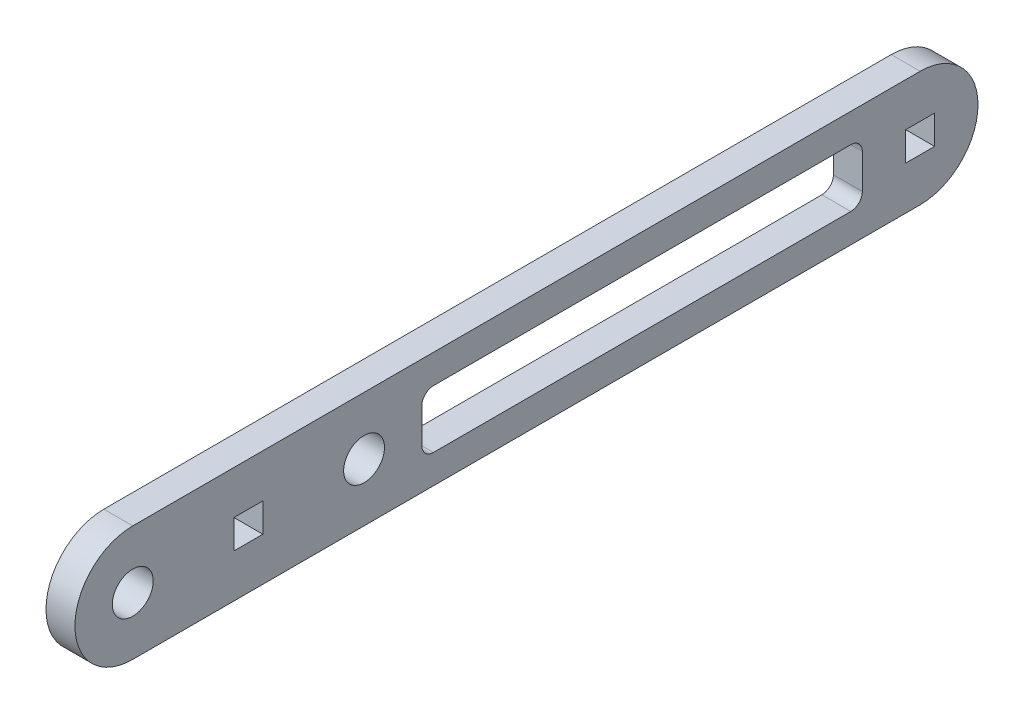
SolidWorks part; units mm, degrees
material "Custom Plastic"
ref_plane "Front Plane" through (0, 0, 0) normal (0, 0, 1) x (1, 0, 0)
ref_plane "Top Plane" through (0, 0, 0) normal (0, 1, 0) x (1, 0, 0)
ref_plane "Right Plane" through (0, 0, 0) normal (1, 0, 0) x (0, 0, -1)
sketch "Sketch1" plane through (0, 0, 0) normal (1, 0, 0) x (0, 0, -1)
  line L0 (0, 0) -> (-73.7616, 0) construction
  line L1 (-88.0491, -1.5875) -> (-84.8741, 1.5875) construction
  line L2 (-72.1741, -1.5875) -> (-75.3491, -1.5875)
  line L3 (-72.1741, -1.5875) -> (-72.1741, 1.5875)
  line L4 (-72.1741, 1.5875) -> (-75.3491, 1.5875)
  line L5 (-75.3491, -1.5875) -> (-75.3491, 1.5875)
  line L6 (-72.1741, -1.5875) -> (-75.3491, 1.5875) construction
  line L7 (-72.1741, 1.5875) -> (-75.3491, -1.5875) construction
  line L8 (-62.6491, -1.5875) -> (-59.4741, 1.5875) construction
  line L9 (-86.4616, 0) -> (-73.7616, 0) construction
  line L10 (-86.4616, 6.35) -> (0, 6.35)
  line L11 (-86.4616, 6.35) -> (-86.4616, 0) construction
  line L12 (0, -6.35) -> (-86.4616, -6.35)
  line L13 (-86.4616, 0) -> (-86.4616, -6.35) construction
  line L14 (-54.7116, 0) -> (-54.7116, 1.905)
  line L15 (-53.4416, 3.175) -> (-7.62, 3.175)
  line L16 (-6.35, 1.905) -> (-6.35, -1.905)
  line L17 (-7.62, -3.175) -> (-53.4416, -3.175)
  line L18 (-54.7116, -1.905) -> (-54.7116, 0)
  line L20 (1.5875, -1.5875) -> (-1.5875, -1.5875)
  line L21 (1.5875, -1.5875) -> (1.5875, 1.5875)
  line L22 (1.5875, 1.5875) -> (-1.5875, 1.5875)
  line L23 (-1.5875, -1.5875) -> (-1.5875, 1.5875)
  line L24 (1.5875, -1.5875) -> (-1.5875, 1.5875) construction
  line L25 (1.5875, 1.5875) -> (-1.5875, -1.5875) construction
  circle A0 centre (-61.0616, 0) radius 2.2451
  circle A1 centre (-86.4616, 0) radius 2.2451
  circle A2 centre (0, 0) radius 2.2451 construction
  arc A3 (-86.4616, 6.35) -> (-86.4616, -6.35) centre (-86.4616, 0) ccw
  arc A4 (0, 6.35) -> (0, -6.35) centre (0, 0) cw
  arc A5 (-7.62, 3.175) -> (-6.35, 1.905) centre (-7.62, 1.905) cw
  arc A6 (-6.35, -1.905) -> (-7.62, -3.175) centre (-7.62, -1.905) cw
  arc A7 (-53.4416, -3.175) -> (-54.7116, -1.905) centre (-53.4416, -1.905) cw
  arc A8 (-54.7116, 1.905) -> (-53.4416, 3.175) centre (-53.4416, 1.905) cw
  circle A9 centre (-73.7616, 0) radius 2.2451 construction
  dimension "D5" = 6.35
  dimension "D9" = 1.27
  dimension "D1" = 73.7616
  dimension "D2" = 3.175
  dimension "D3" = 12.7
  dimension "D4" = 12.7
  dimension "D6" = 6.35
  dimension "D7" = 6.35
  dimension "D8" = 3.175
extrude "Boss-Extrude1" add sketch "Sketch1" along normal blind 3.175
